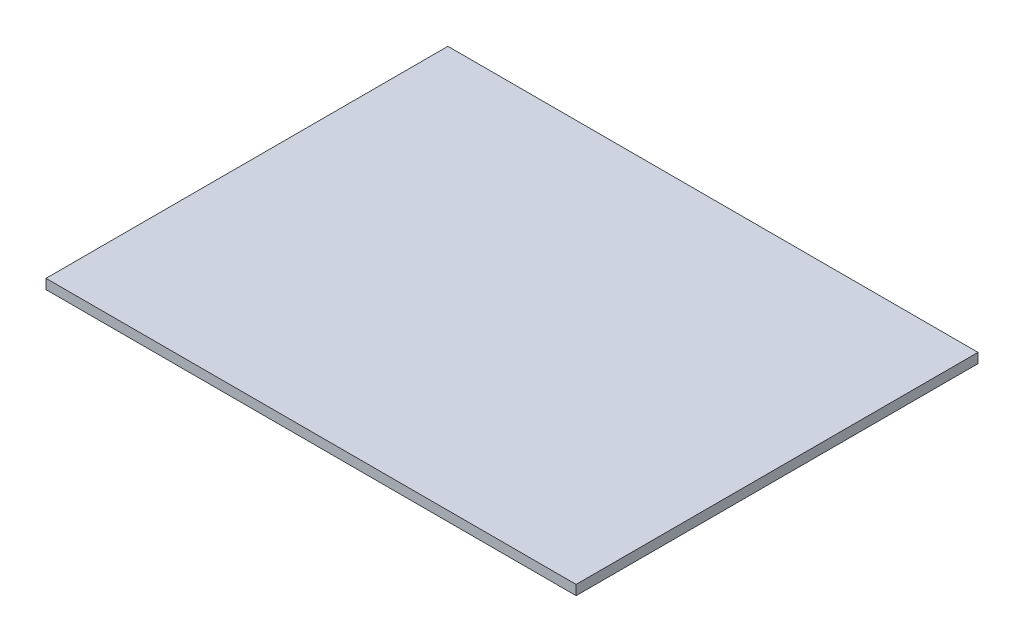
SolidWorks part; units mm, degrees
ref_plane "Alzado" through (0, 0, 0) normal (0, 0, 1) x (1, 0, 0)
ref_plane "Planta" through (0, 0, 0) normal (0, 1, 0) x (1, 0, 0)
ref_plane "Vista lateral" through (0, 0, 0) normal (1, 0, 0) x (0, 0, -1)
sketch "Croquis1" plane through (0, 0, 0) normal (0, 1, 0) x (1, 0, 0)
  line L0 (0, 307.5) -> (0, -307.5) construction
  line L1 (-405.6, -307.5) -> (405.6, -307.5)
  line L2 (-405.6, -307.5) -> (-405.6, 307.5)
  line L3 (-405.6, 307.5) -> (405.6, 307.5)
  line L4 (405.6, -307.5) -> (405.6, 307.5)
  line L5 (-405.6, -307.5) -> (405.6, 307.5) construction
  line L6 (-405.6, 307.5) -> (405.6, -307.5) construction
  line L7 (-405.6, 0) -> (405.6, 0) construction
  point P0 (0, 0)
  point P10 (0, 0)
  dimension "D1" = 811.2
  dimension "D2" = 615
extrude "Saliente-Extruir1" add sketch "Croquis1" along normal blind 15
sketch "Croquis2" plane through (0, 15, 0) normal (0, 1, 0) x (1, 0, 0)
  line L0 (0, 307.5) -> (0, -307.5) construction
  line L1 (405.6, 307.5) -> (-405.6, 307.5) construction
  line L2 (-405.6, -307.5) -> (405.6, -307.5) construction
  line L3 (-405.6, 0) -> (405.6, 0) construction
  line L4 (-405.6, 307.5) -> (-405.6, -307.5) construction
  line L5 (405.6, -307.5) -> (405.6, 307.5) construction
  line L6 (-188, 307.5) -> (-188, -307.5) construction
  line L7 (188, 307.5) -> (188, -307.5) construction
  dimension "D3" = 188
  dimension "D4" = 188
